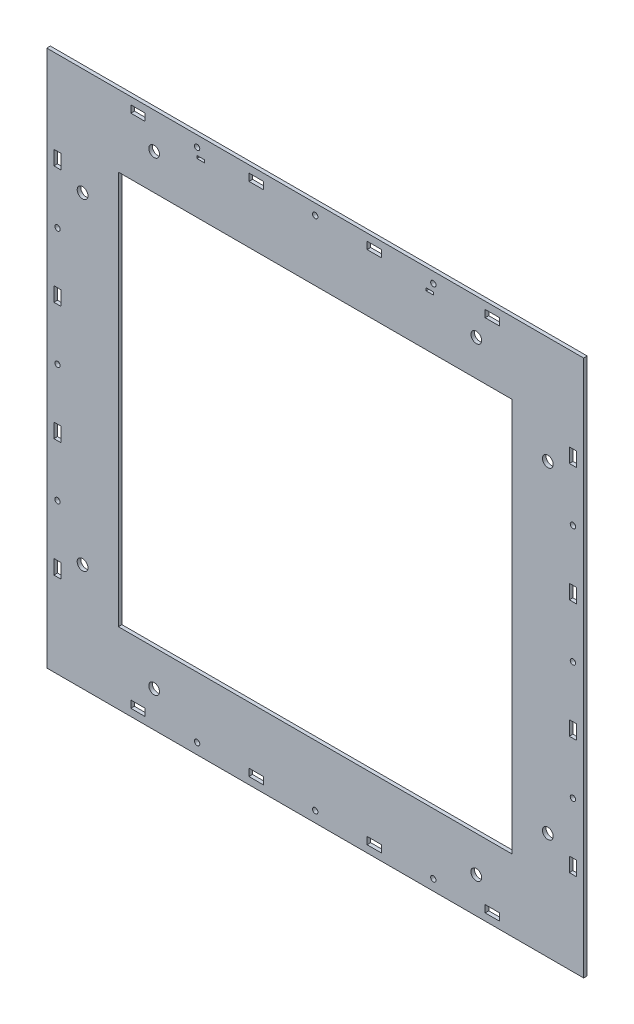
SolidWorks part; units mm, degrees
ref_plane "前视基准面" through (0, 0, 0) normal (0, 0, 1) x (1, 0, 0)
ref_plane "上视基准面" through (0, 0, 0) normal (0, 1, 0) x (1, 0, 0)
ref_plane "右视基准面" through (0, 0, 0) normal (1, 0, 0) x (0, 0, -1)
sketch "草图1" plane through (0, 0, 0) normal (0, 0, 1) x (1, 0, 0)
  line L1 (63.4571, 98.8129) -> (67.4571, 98.8129)
  line L3 (67.4571, 98.8129) -> (67.4571, 97.3129)
  line L4 (151.4571, -41.1871) -> (151.4571, 108.8129)
  line L5 (151.4571, 108.8129) -> (-148.5429, 108.8129)
  line L6 (-148.5429, 108.8129) -> (-148.5429, -191.1871)
  line L7 (-148.5429, -191.1871) -> (151.4571, -191.1871)
  line L8 (151.4571, -191.1871) -> (151.4571, -41.1871)
  line L9 (-148.5429, -41.1871) -> (-161.9412, -41.1871) construction
  line L10 (1.4571, -191.1871) -> (1.4571, -181.0361) construction
  line L11 (67.4571, 97.3129) -> (63.4571, 97.3129)
  line L12 (63.4571, 97.3129) -> (63.4571, 98.8129)
  line L13 (-64.5429, 98.8129) -> (-64.5429, 97.3129)
  line L14 (-64.5429, 97.3129) -> (-60.5429, 97.3129)
  line L15 (-60.5429, 97.3129) -> (-60.5429, 98.8129)
  line L16 (-60.5429, 98.8129) -> (-64.5429, 98.8129)
  circle A6 centre (1.4571, -21.1871) radius 241.4173 construction
  dimension "D2" = 300
  dimension "D3" = 300
extrude "凸台-拉伸1" add sketch "草图1" along normal blind 2
sketch "草图3" plane through (0, 0, 2) normal (0, 0, 1) x (1, 0, 0)
  line L1 (96.4421, -183.1721) -> (104.4721, -183.1721)
  line L13 (1.4571, -191.1871) -> (1.4571, -185.1871) construction
  line L14 (-148.5429, -191.1871) -> (151.4571, -191.1871) construction
  line L15 (1.4571, -185.1871) -> (34.4571, -185.1871) construction
  line L16 (34.4571, -185.1871) -> (67.4571, -185.1871) construction
  line L17 (30.4421, -183.1721) -> (38.4721, -183.1721)
  line L18 (30.4421, -183.1721) -> (30.4421, -187.2021)
  line L19 (30.4421, -187.2021) -> (38.4721, -187.2021)
  line L20 (38.4721, -183.1721) -> (38.4721, -187.2021)
  line L21 (30.4421, -183.1721) -> (38.4721, -187.2021) construction
  line L22 (30.4421, -187.2021) -> (38.4721, -183.1721) construction
  line L23 (67.4571, -185.1871) -> (100.4571, -185.1871) construction
  line L24 (96.4421, -183.1721) -> (96.4421, -187.2021)
  line L25 (96.4421, -187.2021) -> (104.4721, -187.2021)
  line L26 (96.4421, -187.2021) -> (104.4721, -183.1721) construction
  line L27 (104.4721, -187.2021) -> (104.4721, -183.1721)
  line L28 (-35.5579, -183.1721) -> (-35.5579, -187.2021)
  line L29 (-27.5279, -183.1721) -> (-35.5579, -183.1721)
  line L30 (-27.5279, -183.1721) -> (-27.5279, -187.2021)
  line L31 (-27.5279, -187.2021) -> (-35.5579, -187.2021)
  line L32 (-93.5279, -183.1721) -> (-93.5279, -187.2021)
  line L33 (-101.5579, -187.2021) -> (-101.5579, -183.1721)
  line L34 (-93.5279, -183.1721) -> (-101.5579, -183.1721)
  line L35 (-93.5279, -187.2021) -> (-101.5579, -187.2021)
  line L36 (-140.5279, 53.7979) -> (-140.5279, 61.8279)
  line L37 (-144.5579, 53.7979) -> (-144.5579, 61.8279)
  line L38 (-144.5579, 61.8279) -> (-140.5279, 61.8279)
  line L39 (-140.5279, 53.7979) -> (-144.5579, 53.7979)
  line L40 (-140.5279, -12.2021) -> (-140.5279, -4.1721)
  line L41 (-140.5279, -4.1721) -> (-144.5579, -4.1721)
  line L42 (-144.5579, -12.2021) -> (-144.5579, -4.1721)
  line L43 (-140.5279, -12.2021) -> (-144.5579, -12.2021)
  line L44 (-140.5279, -70.1721) -> (-144.5579, -70.1721)
  line L45 (-140.5279, -70.1721) -> (-140.5279, -78.2021)
  line L46 (-144.5579, -70.1721) -> (-144.5579, -78.2021)
  line L47 (-140.5279, -78.2021) -> (-144.5579, -78.2021)
  line L48 (-140.5279, -136.1721) -> (-140.5279, -144.2021)
  line L49 (-144.5579, -136.1721) -> (-144.5579, -144.2021)
  line L50 (-140.5279, -136.1721) -> (-144.5579, -136.1721)
  line L51 (-144.5579, -144.2021) -> (-140.5279, -144.2021)
  line L52 (96.4421, 100.7979) -> (104.4721, 100.7979)
  line L53 (96.4421, 104.8279) -> (104.4721, 104.8279)
  line L54 (104.4721, 104.8279) -> (104.4721, 100.7979)
  line L55 (96.4421, 100.7979) -> (96.4421, 104.8279)
  line L56 (30.4421, 100.7979) -> (38.4721, 100.7979)
  line L57 (38.4721, 100.7979) -> (38.4721, 104.8279)
  line L58 (30.4421, 104.8279) -> (38.4721, 104.8279)
  line L59 (30.4421, 100.7979) -> (30.4421, 104.8279)
  line L60 (-27.5279, 100.7979) -> (-27.5279, 104.8279)
  line L61 (-27.5279, 100.7979) -> (-35.5579, 100.7979)
  line L62 (-27.5279, 104.8279) -> (-35.5579, 104.8279)
  line L63 (-35.5579, 100.7979) -> (-35.5579, 104.8279)
  line L64 (-93.5279, 100.7979) -> (-101.5579, 100.7979)
  line L65 (-93.5279, 104.8279) -> (-101.5579, 104.8279)
  line L66 (-93.5279, 100.7979) -> (-93.5279, 104.8279)
  line L67 (-101.5579, 104.8279) -> (-101.5579, 100.7979)
  line L68 (143.4421, -136.1721) -> (143.4421, -144.2021)
  line L69 (147.4721, -136.1721) -> (147.4721, -144.2021)
  line L70 (147.4721, -144.2021) -> (143.4421, -144.2021)
  line L71 (143.4421, -136.1721) -> (147.4721, -136.1721)
  line L72 (143.4421, -70.1721) -> (143.4421, -78.2021)
  line L73 (143.4421, -78.2021) -> (147.4721, -78.2021)
  line L74 (147.4721, -70.1721) -> (147.4721, -78.2021)
  line L75 (143.4421, -70.1721) -> (147.4721, -70.1721)
  line L76 (143.4421, -12.2021) -> (147.4721, -12.2021)
  line L77 (143.4421, -12.2021) -> (143.4421, -4.1721)
  line L78 (147.4721, -12.2021) -> (147.4721, -4.1721)
  line L79 (143.4421, -4.1721) -> (147.4721, -4.1721)
  line L80 (143.4421, 53.7979) -> (143.4421, 61.8279)
  line L81 (147.4721, 53.7979) -> (147.4721, 61.8279)
  line L82 (143.4421, 53.7979) -> (147.4721, 53.7979)
  line L83 (147.4721, 61.8279) -> (143.4421, 61.8279)
  line L84 (50.9571, -185.1871) -> (50.9571, -170.1871) construction
  line L85 (17.9571, -185.1871) -> (17.9571, -170.1871) construction
  line L86 (-48.0429, -170.1871) -> (-15.0429, -170.1871) construction
  line L91 (-31.5429, -170.1871) -> (-31.5429, -155.1871) construction
  circle A0 centre (1.4571, -185.1871) radius 1.5
  circle A1 centre (67.4571, -185.1871) radius 1.5
  circle A2 centre (-64.5429, -185.1871) radius 1.5
  circle A3 centre (-142.5429, 24.8129) radius 1.5
  circle A4 centre (-142.5429, -41.1871) radius 1.5
  circle A5 centre (-142.5429, -107.1871) radius 1.5
  circle A6 centre (67.4571, 102.8129) radius 1.5
  circle A7 centre (1.4571, 102.8129) radius 1.5
  circle A8 centre (-64.5429, 102.8129) radius 1.5
  circle A9 centre (145.4571, -107.1871) radius 1.5
  circle A10 centre (145.4571, -41.1871) radius 1.5
  circle A11 centre (145.4571, 24.8129) radius 1.5
  circle A15 centre (17.9571, -170.1871) radius 2 construction
  circle A16 centre (-15.0429, -170.1871) radius 2 construction
  circle A17 centre (50.9571, -170.1871) radius 1.5 construction
  circle A18 centre (-48.0429, -170.1871) radius 1.5 construction
  circle A19 centre (-31.5429, -155.1871) radius 1.5 construction
  circle A20 centre (34.4571, -155.1871) radius 1.5 construction
  circle A22 centre (1.4571, -155.1871) radius 2 construction
  circle A23 centre (1.4571, -41.1871) radius 67.5 construction
  circle A24 centre (1.4571, -108.6871) radius 1.65
  circle A25 centre (-46.2726, -88.9169) radius 1.65
  circle A26 centre (-66.0429, -41.1871) radius 1.65
  circle A27 centre (-46.2726, 6.5426) radius 1.65
  circle A28 centre (1.4571, 26.3129) radius 1.65
  circle A29 centre (49.1869, 6.5426) radius 1.65
  circle A30 centre (68.9571, -41.1871) radius 1.65
  circle A31 centre (49.1869, -88.9169) radius 1.65
  circle A32 centre (1.4571, -125.1871) radius 1.5
  dimension "D1" = 8.03
  dimension "D3" = 4
  dimension "D4" = 8
  dimension "D5" = 30
  dimension "D6" = 3.3
  dimension "D2" = 4.03
extrude "切除-拉伸2" cut sketch "草图3" against normal blind 4
sketch "草图6" plane through (0, 0, 2) normal (0, 0, 1) x (1, 0, 0)
sketch "草图7" plane through (0, 0, 2) normal (0, 0, 1) x (1, 0, 0)
  line L5 (-148.5429, -171.1871) -> (151.4571, -171.1871) construction
  line L6 (-148.5429, 108.8129) -> (-148.5429, -191.1871) construction
  line L7 (151.4571, -191.1871) -> (151.4571, 108.8129) construction
  line L8 (-148.5429, -191.1871) -> (151.4571, -191.1871) construction
  circle A0 centre (-88.5429, -171.1871) radius 3
  circle A1 centre (91.4571, -171.1871) radius 3
  circle A2 centre (-128.5429, 48.8129) radius 3
  circle A3 centre (-128.5429, -131.1871) radius 3
  circle A4 centre (91.4571, 88.8129) radius 3
  circle A5 centre (-88.5429, 88.8129) radius 3
  circle A6 centre (131.4571, -131.1871) radius 3
  circle A7 centre (131.4571, 48.8129) radius 3
  dimension "D2" = 6
  dimension "D4" = 60
  dimension "D1" = 20
  dimension "D3" = 60
  dimension "D5" = 4
extrude "切除-拉伸3" cut sketch "草图7" against normal blind 10
sketch "草图8" plane through (0, 0, 2) normal (0, 0, 1) x (1, 0, 0)
  line L1 (111.4571, -151.1871) -> (-108.5429, -151.1871)
  line L2 (111.4571, -151.1871) -> (111.4571, 68.8129)
  line L3 (111.4571, 68.8129) -> (-108.5429, 68.8129)
  line L4 (-108.5429, -151.1871) -> (-108.5429, 68.8129)
  line L5 (111.4571, -151.1871) -> (-108.5429, 68.8129) construction
  line L6 (111.4571, 68.8129) -> (-108.5429, -151.1871) construction
  point P0 (1.4571, -41.1871)
  dimension "D2" = 220
extrude "切除-拉伸4" cut sketch "草图8" against normal blind 4
